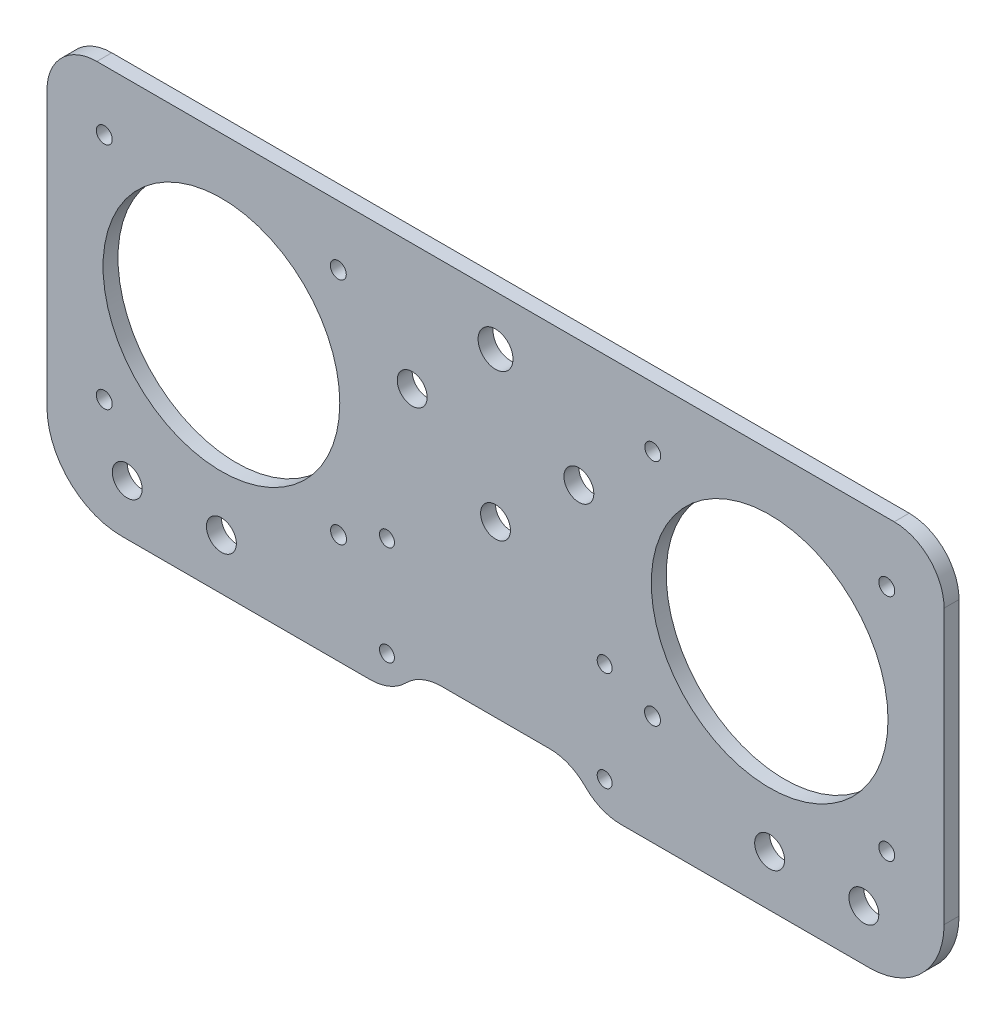
SolidWorks part; units mm, degrees
material "Acrylic (Medium-high impact)"
ref_plane "Front Plane" through (0, 0, 0) normal (0, 0, 1) x (1, 0, 0)
ref_plane "Top Plane" through (0, 0, 0) normal (0, 1, 0) x (1, 0, 0)
ref_plane "Right Plane" through (0, 0, 0) normal (1, 0, 0) x (0, 0, -1)
sketch "Sketch1" plane through (0, 0, 0) normal (0, 0, 1) x (1, 0, 0)
  line L0 (0, 40) -> (0, -40) construction
  line L1 (-90, 40) -> (90, 40)
  line L2 (-90, 40) -> (-90, -40)
  line L3 (-90, -40) -> (90, -40)
  line L4 (90, 40) -> (90, -40)
  line L5 (90, 0) -> (-90, 0) construction
  line L6 (90, 5) -> (-90, 5) construction
  line L7 (-90, 5) -> (-55, 5) construction
  line L8 (90, 5) -> (55, 5) construction
  circle A0 centre (55, 5) radius 23.75
  circle A1 centre (-55, 5) radius 23.75
  point P8 (0, 0)
extrude "Boss-Extrude1" add sketch "Sketch1" along normal blind 3
sketch "Sketch2" plane through (0, 0, 3) normal (0, 0, 1) x (1, 0, 0)
  line L1 (-55, 5) -> (49945, 5) construction
  line L2 (55, 5) -> (55, -49995) construction
  line L3 (-25, 5) -> (-25, -49995) construction
  line L4 (25, 5) -> (25, -49995) construction
  line L7 (-19, 5) -> (-19, -49995) construction
  line L8 (19, 5) -> (19, -49995) construction
  line L9 (-55, 2) -> (49945, 2) construction
  line L10 (-55, 8) -> (49945, 8) construction
  line L11 (-55, -4) -> (49945, -4) construction
  line L12 (-55, 14) -> (49945, 14) construction
  line L14 (52, 5) -> (52, -49995) construction
  line L16 (58, 5) -> (58, -49995) construction
  line L18 (46, 5) -> (46, -49995) construction
  line L20 (64, 5) -> (64, -49995) construction
sketch "Sketch3" plane through (0, 0, 3) normal (0, 0, 1) x (1, 0, 0)
  line L0 (0, 40) -> (0, -40) construction
  line L1 (90, 40) -> (-90, 40) construction
  line L2 (-90, -40) -> (90, -40) construction
  line L3 (0, -40) -> (0, -34) construction
  line L4 (0, -34) -> (15, -34) construction
  line L5 (0, -34) -> (-15, -34) construction
  line L6 (-15, -34) -> (-15, -40) construction
  line L7 (-15, -40) -> (-21, -40) construction
  line L8 (-21, -40) -> (-15, -34) construction
  line L9 (15, -34) -> (15, -40) construction
  line L10 (15, -40) -> (21, -40) construction
  line L11 (21, -40) -> (15, -34) construction
  line L12 (-21, -40) -> (-15, -34)
  line L13 (-15, -34) -> (15, -34)
  line L14 (15, -34) -> (21, -40)
  line L15 (21, -40) -> (-21, -40)
extrude "Cut-Extrude2" cut sketch "Sketch3" against normal blind 3
sketch "Sketch4" plane through (0, 0, 3) normal (0, 0, 1) x (1, 0, 0)
  line L0 (-55, -18) -> (49945, -18) construction
  line L1 (-55, 28) -> (49945, 28) construction
  line L2 (0, 0) -> (0, -50000) construction
  line L3 (-55, -18.75) -> (-55, 49981.25) construction
  line L4 (-31.5, -18.75) -> (-31.5, 49981.25) construction
  line L5 (-78.5, -18.75) -> (-78.5, 49981.25) construction
  line L6 (-55, 5) -> (49945, 5) construction
  circle A0 centre (-78.5, 28) radius 1.6
  circle A1 centre (-31.5459, 28) radius 1.6
  circle A2 centre (-31.5, -18) radius 1.6
  circle A3 centre (-78.5, -18) radius 1.6
  circle A4 centre (31.5, -18) radius 1.6
  circle A5 centre (31.5459, 28) radius 1.6
  circle A6 centre (78.5, 28) radius 1.6
  circle A7 centre (78.5, -18) radius 1.6
extrude "Cut-Extrude3" cut sketch "Sketch4" against normal blind 3
sketch "Sketch7" plane through (0, 0, 3) normal (0, 0, 1) x (1, 0, 0)
  line L0 (0, 0) -> (0, -50000) construction
  line L1 (0, 0) -> (0, 30) construction
  circle A0 centre (0, 0) radius 3
  circle A1 centre (0, 30) radius 3.5
extrude "Cut-Extrude4" cut sketch "Sketch7" against normal blind 3
fillet "Fillet1" radius 10 2 edges at (90, 40, 1.5) (-90, 40, 1.5)
fillet "Fillet2" radius 15 2 edges at (90, -40, 1.5) (-90, -40, 1.5)
fillet "Fillet3" radius 10 4 edges at (21, -40, 1.5) (15, -34, 1.5) (-15, -34, 1.5) (-21, -40, 1.5)
sketch "Sketch8" plane through (0, 0, 3) normal (0, 0, 1) x (1, 0, 0)
  line L0 (-29.9459, -972) -> (-29.9459, 49028) construction
  line L1 (29.9459, -972) -> (29.9459, 49028) construction
  line L2 (-3.5, -970) -> (-3.5, 49030) construction
  line L3 (3.5, -970) -> (3.5, 49030) construction
  line L4 (-1000, 26.5) -> (49000, 26.5) construction
  line L5 (-1000, 3) -> (49000, 3) construction
  line L6 (-29.9459, 26.5) -> (-3.5, 3) construction
  line L7 (-3.5, 26.5) -> (-29.9459, 3) construction
  line L8 (17.9289, -36.9289) -> (18.0711, -37.0711)
  line L9 (25.1421, -40) -> (75, -40)
  line L10 (90, -25) -> (90, 30)
  line L11 (80, 40) -> (-80, 40)
  line L12 (-90, 30) -> (-90, -25)
  line L13 (-75, -40) -> (-25.1421, -40)
  line L14 (-18.0711, -37.0711) -> (-17.9289, -36.9289)
  line L15 (-10.8579, -34) -> (10.8579, -34)
  line L16 (17.9289, -36.9289) -> (18.0711, -37.0711)
  line L17 (25.1421, -40) -> (75, -40)
  line L18 (90, -25) -> (90, 30)
  line L19 (80, 40) -> (-80, 40)
  line L20 (-90, 30) -> (-90, -25)
  line L21 (-75, -40) -> (-25.1421, -40)
  line L22 (-18.0711, -37.0711) -> (-17.9289, -36.9289)
  line L23 (-10.8579, -34) -> (10.8579, -34)
  line L24 (3.5, 26.5) -> (29.9459, 3) construction
  line L25 (-1078.5, -19.6) -> (48921.5, -19.6) construction
  line L26 (29.9459, 26.5) -> (3.5, 3) construction
  line L27 (-76.9, -1018) -> (-76.9, 48982) construction
  line L28 (0, -1000) -> (0, 49000) construction
  line L29 (-33.1, -1018) -> (-33.1, 48982) construction
  line L30 (-76.9, -19.6) -> (-33.1, -40) construction
  line L31 (-55, -29.8) -> (-76.9, -29.8) construction
  line L32 (-76.9, -29.8) -> (-73.9, -29.8) construction
  circle A0 centre (-55, -29.8) radius 3
  circle A1 centre (-73.9, -29.8) radius 3
  circle A2 centre (55, -29.8) radius 3
  circle A3 centre (73.9, -29.8) radius 3
  circle A6 centre (16.7229, 14.75) radius 3
  circle A7 centre (-16.7229, 14.75) radius 3
  arc A8 (18.0711, -37.0711) -> (25.1421, -40) centre (25.1421, -30) ccw
  arc A9 (75, -40) -> (90, -25) centre (75, -25) ccw
  arc A10 (90, 30) -> (80, 40) centre (80, 30) ccw
  arc A11 (-80, 40) -> (-90, 30) centre (-80, 30) ccw
  arc A12 (-90, -25) -> (-75, -40) centre (-75, -25) ccw
  arc A13 (-25.1421, -40) -> (-18.0711, -37.0711) centre (-25.1421, -30) ccw
  arc A14 (-10.8579, -34) -> (-17.9289, -36.9289) centre (-10.8579, -44) ccw
  arc A15 (17.9289, -36.9289) -> (10.8579, -34) centre (10.8579, -44) ccw
  arc A16 (18.0711, -37.0711) -> (25.1421, -40) centre (25.1421, -30) ccw
  arc A17 (75, -40) -> (90, -25) centre (75, -25) ccw
  arc A18 (90, 30) -> (80, 40) centre (80, 30) ccw
  arc A19 (-80, 40) -> (-90, 30) centre (-80, 30) ccw
  arc A20 (-90, -25) -> (-75, -40) centre (-75, -25) ccw
  arc A21 (-25.1421, -40) -> (-18.0711, -37.0711) centre (-25.1421, -30) ccw
  arc A22 (-10.8579, -34) -> (-17.9289, -36.9289) centre (-10.8579, -44) ccw
  arc A23 (17.9289, -36.9289) -> (10.8579, -34) centre (10.8579, -44) ccw
  dimension "D1" = 0
extrude "Cut-Extrude6" cut sketch "Sketch8" against normal blind 10 contours A0 | A1 | A2 | A3 | A7 | A6
sketch "Sketch9" plane through (0, 0, 0) normal (0, 0, -1) x (-1, 0, 0)
  line L0 (-29.9, -1018) -> (-29.9, 48982) construction
  line L1 (-21.9, -1018) -> (-21.9, 48982) construction
  line L2 (-0.0586, -7.3562) -> (-0.0586, -27.3562) construction
  line L3 (-20.198, -13.7701) -> (-20.198, -33.7701) construction
  circle A1 centre (-21.9, -33.7701) radius 1.5
  circle A2 centre (-21.9, -13.7701) radius 1.5
  circle A3 centre (21.7828, -13.7701) radius 1.5
  circle A4 centre (21.7828, -33.7701) radius 1.5
  dimension "D1" = 8
extrude "Cut-Extrude7" cut sketch "Sketch9" against normal blind 10
